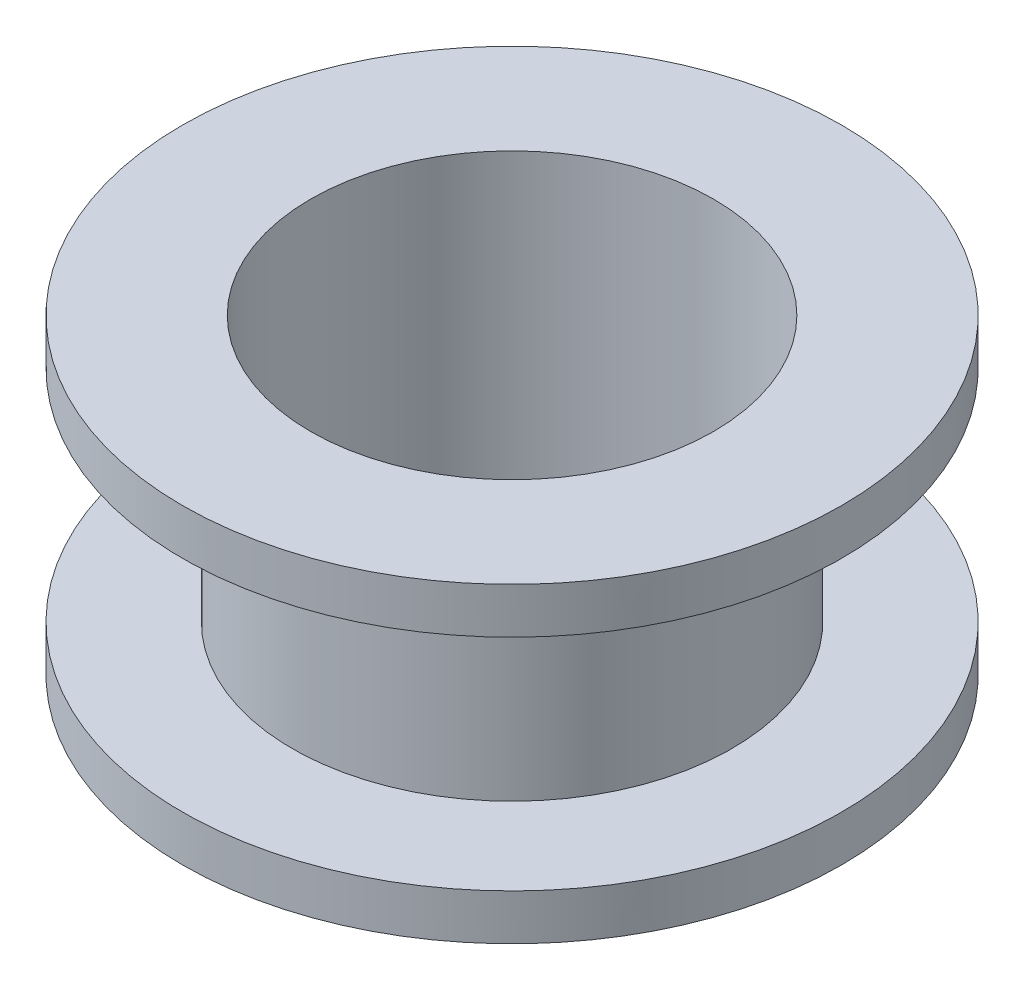
SolidWorks part; units mm, degrees
ref_plane "Front Plane" through (0, 0, 0) normal (0, 0, 1) x (1, 0, 0)
ref_plane "Top Plane" through (0, 0, 0) normal (0, 1, 0) x (1, 0, 0)
ref_plane "Right Plane" through (0, 0, 0) normal (1, 0, 0) x (0, 0, -1)
sketch "Sketch1" plane through (0, 0, 0) normal (0, 1, 0) x (1, 0, 0)
  circle A0 centre (0, 0) radius 9
  circle A1 centre (0, 0) radius 5.5
  dimension "D1" = 18
  dimension "D2" = 11
extrude "Boss-Extrude1" add sketch "Sketch1" along normal blind 8.5
sketch "Sketch4" plane through (0, 0, 0) normal (0, 0, 1) x (1, 0, 0)
  line L0 (9, 0) -> (9, 8.5) construction
  line L1 (9, 7.25) -> (6, 7.25)
  line L2 (9, 7.25) -> (9, 1.25)
  line L3 (9, 1.25) -> (6, 1.25)
  line L4 (6, 7.25) -> (6, 1.25)
  line L5 (-9, 0) -> (9, 0) construction
  line L6 (9, 8.5) -> (-9, 8.5) construction
  line L7 (0, 0) -> (0, 9.9733) construction
  dimension "D1" = 1.25
  dimension "D2" = 1.25
  dimension "D3" = 3
revolve "Cut-Revolve1" cut sketch "Sketch4" angle 360 about L7
